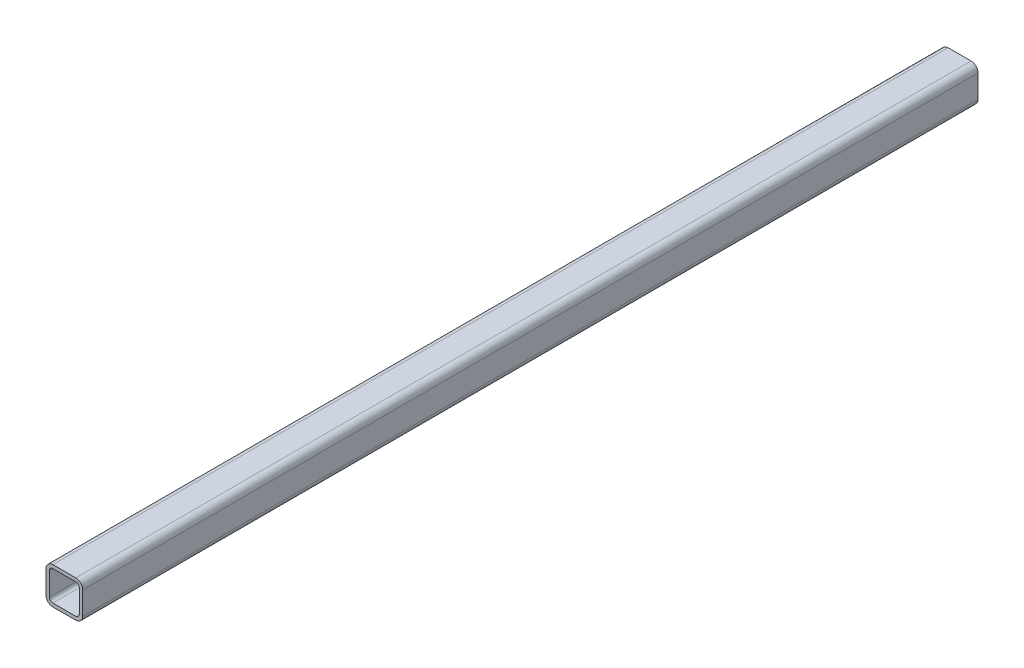
SolidWorks part; units mm, degrees
ref_plane "Płaszczyzna przednia" through (0, 0, 0) normal (0, 0, 1) x (1, 0, 0)
ref_plane "Płaszczyzna górna" through (0, 0, 0) normal (0, 1, 0) x (1, 0, 0)
ref_plane "Płaszczyzna prawa" through (0, 0, 0) normal (1, 0, 0) x (0, 0, -1)
sketch "Szkic1" plane through (0, 0, 0) normal (0, 0, 1) x (1, 0, 0)
  line L1 (9.53, 0) -> (41.27, 0)
  line L2 (0, 9.53) -> (0, 41.27)
  line L3 (9.53, 50.8) -> (41.27, 50.8)
  line L4 (50.8, 9.53) -> (50.8, 41.27)
  line L5 (9.52, 46.04) -> (41.28, 46.04)
  line L6 (4.76, 41.28) -> (4.76, 9.52)
  line L7 (9.52, 4.76) -> (41.28, 4.76)
  line L8 (46.04, 41.28) -> (46.04, 9.52)
  arc A0 (4.76, 9.52) -> (9.52, 4.76) centre (9.52, 9.52) ccw
  arc A1 (41.28, 4.76) -> (46.04, 9.52) centre (41.28, 9.52) ccw
  arc A2 (46.04, 41.28) -> (41.28, 46.04) centre (41.28, 41.28) ccw
  arc A3 (4.76, 41.28) -> (9.52, 46.04) centre (9.52, 41.28) cw
  arc A4 (41.27, 50.8) -> (50.8, 41.27) centre (41.27, 41.27) cw
  arc A5 (50.8, 9.53) -> (41.27, 0) centre (41.27, 9.53) cw
  arc A6 (9.53, 0) -> (0, 9.53) centre (9.53, 9.53) cw
  arc A7 (0, 41.27) -> (9.53, 50.8) centre (9.53, 41.27) cw
  dimension "D7" = 4.76
  dimension "D8" = 9.53
  dimension "D1" = 50.8
  dimension "D2" = 50.8
  dimension "D3" = 41.28
  dimension "D4" = 41.28
  dimension "D5" = 4.76
  dimension "D6" = 4.76
extrude "Dodanie-wyciągnięcie1" add sketch "Szkic1" along normal blind 1239.2
